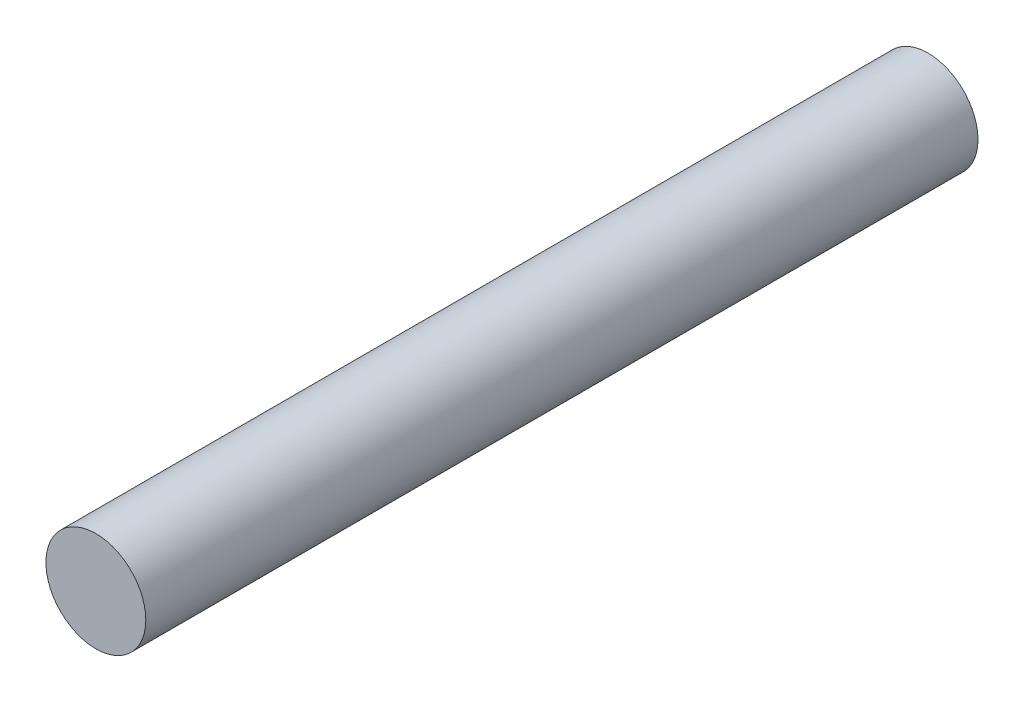
SolidWorks part; units mm, degrees
ref_plane "Front Plane" through (0, 0, 0) normal (0, 0, 1) x (1, 0, 0)
ref_plane "Top Plane" through (0, 0, 0) normal (0, 1, 0) x (1, 0, 0)
ref_plane "Right Plane" through (0, 0, 0) normal (1, 0, 0) x (0, 0, -1)
sketch "Sketch1" plane through (0, 0, 0) normal (0, 0, 1) x (1, 0, 0)
  circle A0 centre (-26.7171, 0) radius 3
extrude "Boss-Extrude1" add sketch "Sketch1" along normal blind 50
